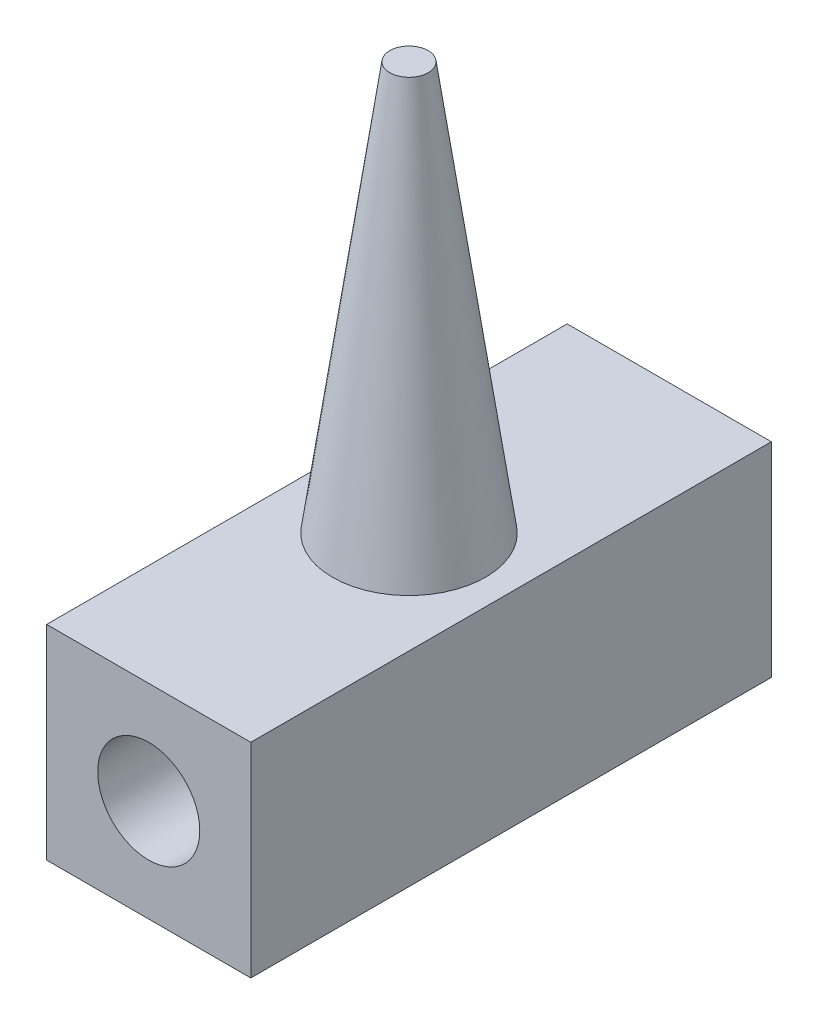
SolidWorks part; units mm, degrees
ref_plane "Front Plane" through (0, 0, 0) normal (0, 0, 1) x (1, 0, 0)
ref_plane "Top Plane" through (0, 0, 0) normal (0, 1, 0) x (1, 0, 0)
ref_plane "Right Plane" through (0, 0, 0) normal (1, 0, 0) x (0, 0, -1)
sketch "Sketch2" plane through (0, 0, 0) normal (0, 0, 1) x (1, 0, 0)
  line L1 (-24.75, 12.75) -> (-4.75, 12.75)
  line L2 (-24.75, 12.75) -> (-24.75, -7.25)
  line L3 (-24.75, -7.25) -> (-4.75, -7.25)
  line L4 (-4.75, 12.75) -> (-4.75, -7.25)
  dimension "D1" = 20
  dimension "D2" = 20
extrude "Boss-Extrude1" add sketch "Sketch2" along normal blind 51
sketch "Sketch3" plane through (0, 0, 51) normal (0, 0, 1) x (1, 0, 0)
  line L0 (-24.75, 12.75) -> (-4.75, -7.25) construction
  line L1 (-24.75, -7.25) -> (-4.75, 12.75) construction
  circle A0 centre (-14.75, 2.75) radius 5
  dimension "D1" = 10
extrude "Cut-Extrude1" cut sketch "Sketch3" against normal blind 51 contours A0
sketch "Sketch4" plane through (0, 12.75, 0) normal (0, 1, 0) x (1, 0, 0)
  line L0 (-24.75, 0) -> (-4.75, -51) construction
  circle A0 centre (-14.75, -25.5) radius 7.5
  dimension "D1" = 15
extrude "Boss-Extrude2" add sketch "Sketch4" along normal blind 40 draft 8
